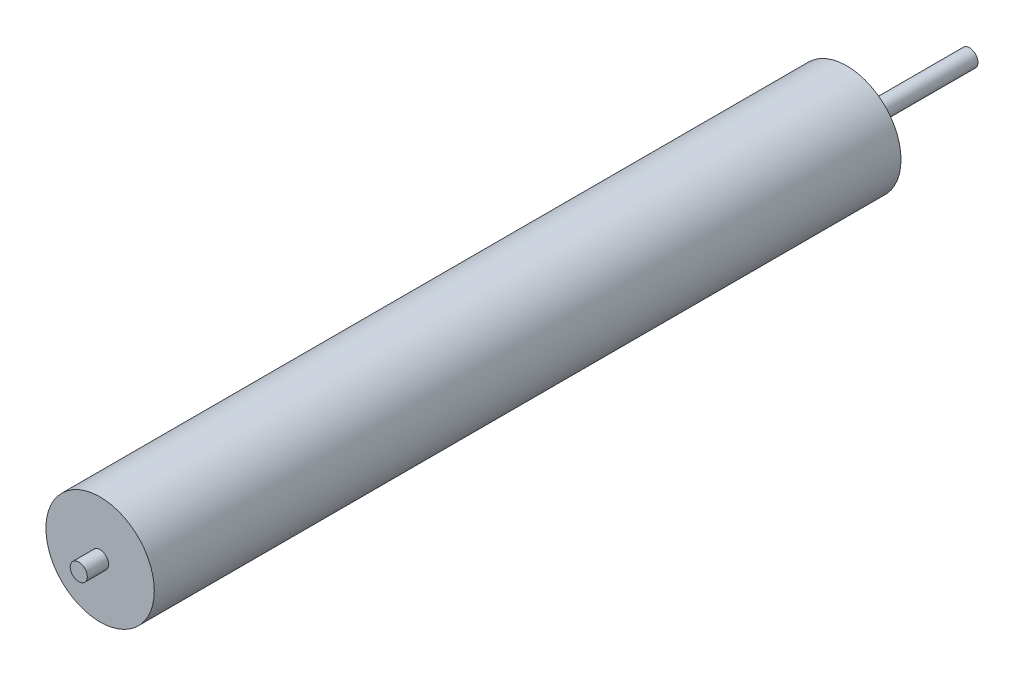
SolidWorks part; units mm, degrees
ref_plane "Alzado" through (0, 0, 0) normal (0, 0, 1) x (1, 0, 0)
ref_plane "Planta" through (0, 0, 0) normal (0, 1, 0) x (1, 0, 0)
ref_plane "Vista lateral" through (0, 0, 0) normal (1, 0, 0) x (0, 0, -1)
sketch "Sketch1" plane through (0, 0, 0) normal (0, 0, 1) x (1, 0, 0)
  circle A0 centre (0, 0) radius 50.8
  dimension "D1" = 101.6
extrude "Boss-Extrude1" add sketch "Sketch1" along normal mid plane 700
sketch "Sketch2" plane through (0, 0, 0) normal (0, 0, 1) x (1, 0, 0)
  circle A0 centre (0, 0) radius 8
  dimension "D1" = 16
extrude "Boss-Extrude2" add sketch "Sketch2" along normal mid plane 740 contours A0
sketch "Sketch3" plane through (0, 0, -370) normal (0, 0, -1) x (-1, 0, 0)
  circle A1 centre (0, 0) radius 8
  circle A2 centre (0, 0) radius 8
  dimension "D1" = 0
extrude "Boss-Extrude3" add sketch "Sketch3" along normal blind 95
